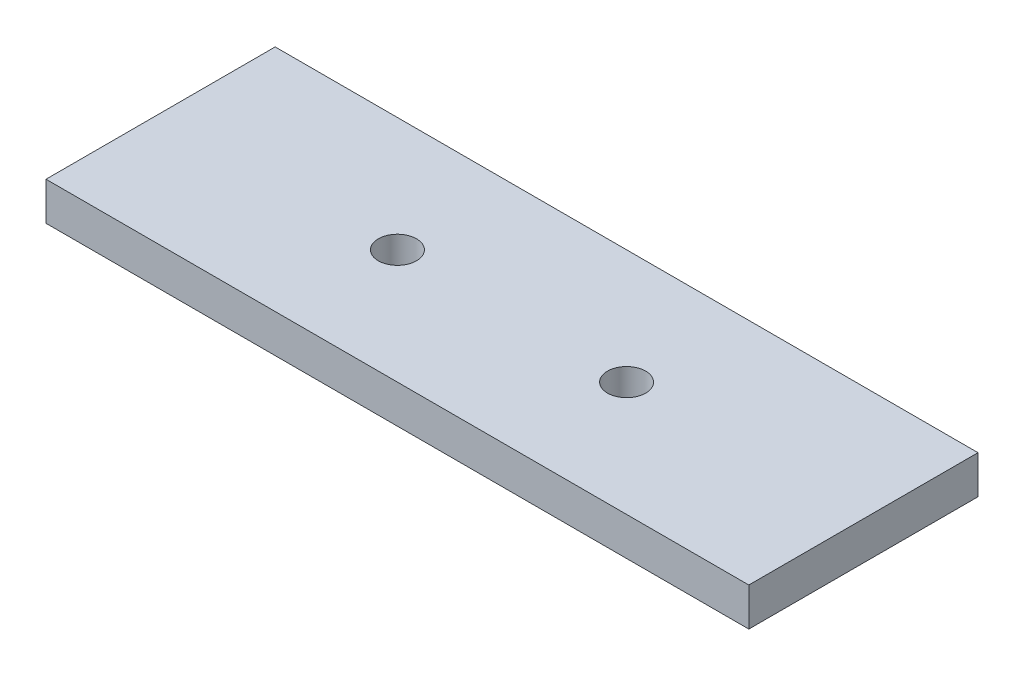
SolidWorks part; units mm, degrees
ref_plane "Front" through (0, 0, 0) normal (0, 0, 1) x (1, 0, 0)
ref_plane "Top" through (0, 0, 0) normal (0, 1, 0) x (1, 0, 0)
ref_plane "Right" through (0, 0, 0) normal (1, 0, 0) x (0, 0, -1)
sketch "Sketch1" plane through (0, 0, 0) normal (0, 1, 0) x (1, 0, 0)
  line L1 (-46, -15) -> (46, -15)
  line L2 (-46, -15) -> (-46, 15)
  line L3 (-46, 15) -> (46, 15)
  line L4 (46, -15) -> (46, 15)
  line L5 (-46, -15) -> (46, 15) construction
  line L6 (-46, 15) -> (46, -15) construction
  point P0 (0, 0)
  dimension "D1" = 30
  dimension "D2" = 92
extrude "Boss-Extrude1" add sketch "Sketch1" along normal blind 5
sketch "Sketch2" plane through (0, 5, 0) normal (0, 1, 0) x (1, 0, 0)
  line L0 (46, -15) -> (46, 15) construction
  circle A0 centre (15, 0) radius 2.5
  circle A1 centre (-15, 0) radius 2.5
  dimension "D2" = 5
  dimension "D3" = 5
  dimension "D1" = 31
  dimension "D4" = 30
extrude "Cut-Extrude1" cut sketch "Sketch2" against normal through all
